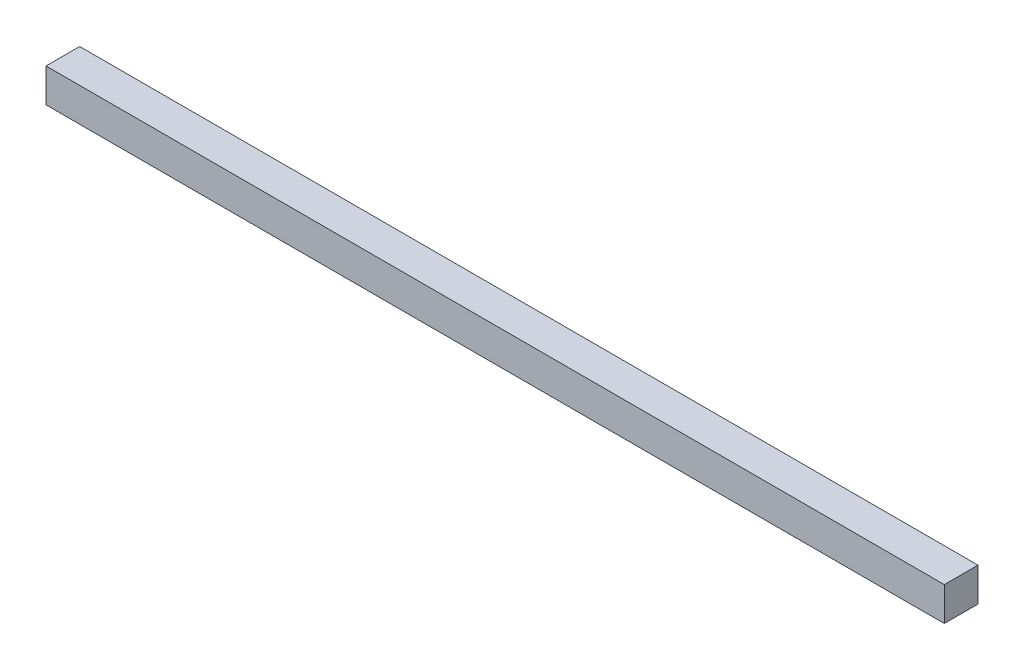
SolidWorks part; units mm, degrees
ref_plane "Front Plane" through (0, 0, 0) normal (0, 0, 1) x (1, 0, 0)
ref_plane "Top Plane" through (0, 0, 0) normal (0, 1, 0) x (1, 0, 0)
ref_plane "Right Plane" through (0, 0, 0) normal (1, 0, 0) x (0, 0, -1)
sketch "Sketch1" plane through (0, 0, 0) normal (0, 1, 0) x (1, 0, 0)
  line L1 (0, 0) -> (800, 0)
  line L2 (0, 0) -> (0, 30)
  line L3 (0, 30) -> (800, 30)
  line L4 (800, 0) -> (800, 30)
  dimension "D1" = 30
  dimension "D2" = 800
extrude "Boss-Extrude1" add sketch "Sketch1" along normal blind 30
